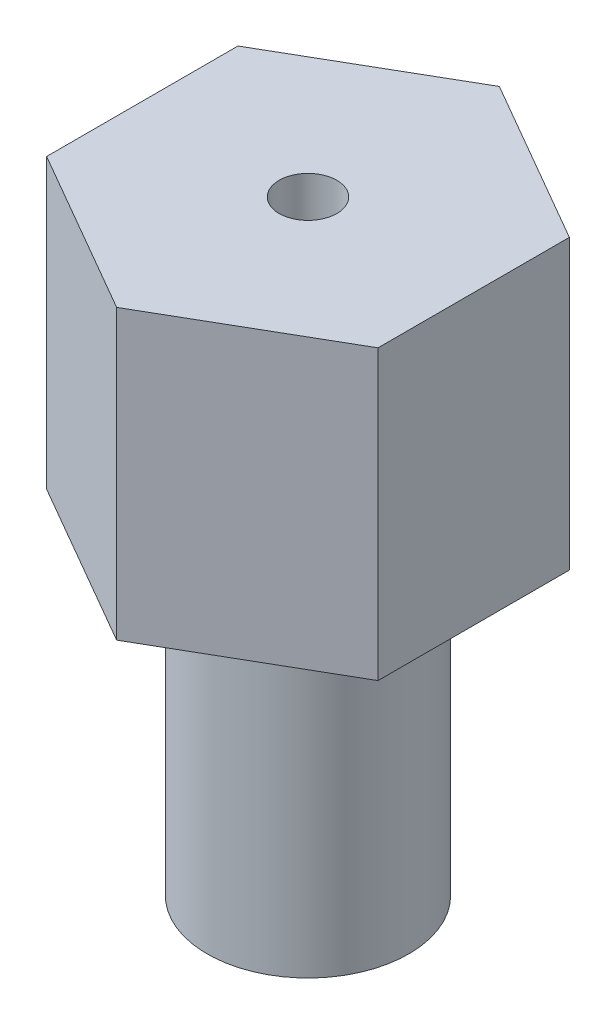
SolidWorks part; units mm, degrees
ref_plane "Alzado" through (0, 0, 0) normal (0, 0, 1) x (1, 0, 0)
ref_plane "Planta" through (0, 0, 0) normal (0, 1, 0) x (1, 0, 0)
ref_plane "Vista lateral" through (0, 0, 0) normal (1, 0, 0) x (0, 0, -1)
sketch "Croquis1" plane through (0, 0, 0) normal (0, 1, 0) x (1, 0, 0)
  line L1 (0, 6.6395) -> (-5.75, 3.3198)
  line L2 (-5.75, 3.3198) -> (-5.75, -3.3198)
  line L3 (-5.75, -3.3198) -> (0, -6.6395)
  line L4 (0, -6.6395) -> (5.75, -3.3198)
  line L5 (5.75, -3.3198) -> (5.75, 3.3198)
  line L6 (5.75, 3.3198) -> (0, 6.6395)
  circle A0 centre (0, 0) radius 5.75 construction
  dimension "D1" = 11.5
extrude "Saliente-Extruir1" add sketch "Croquis1" along normal blind 10
sketch "Croquis2" plane through (0, 0, 0) normal (0, -1, 0) x (1, 0, 0)
  circle A0 centre (0, 0) radius 3.5
  dimension "D1" = 7
extrude "Saliente-Extruir2" add sketch "Croquis2" along normal blind 11
sketch "Croquis3" plane through (0, -11, 0) normal (0, -1, 0) x (1, 0, 0)
  circle A0 centre (0, 0) radius 1
  dimension "D1" = 2
extrude "Cortar-Extruir1" cut sketch "Croquis3" against normal blind 40
